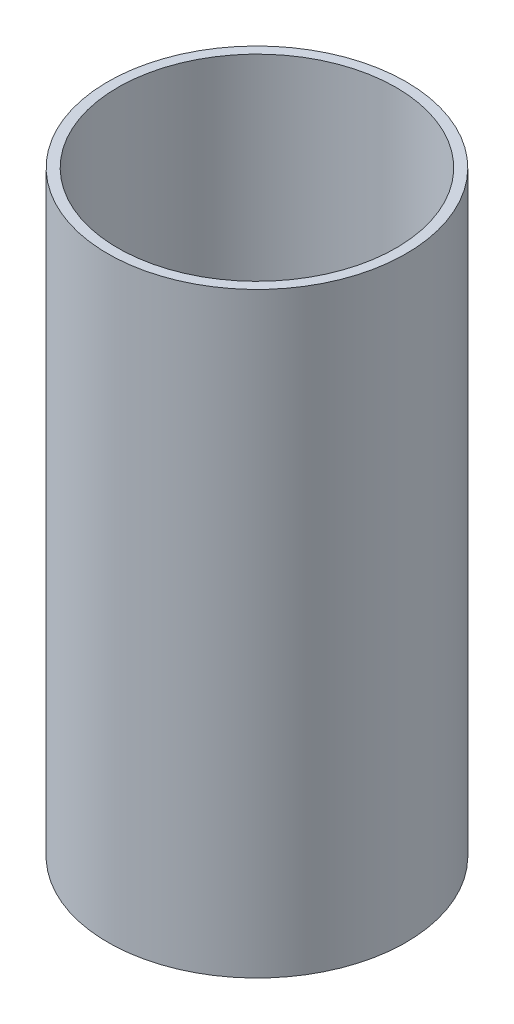
SolidWorks part; units mm, degrees
ref_plane "前视基准面" through (0, 0, 0) normal (0, 0, 1) x (1, 0, 0)
ref_plane "上视基准面" through (0, 0, 0) normal (0, 1, 0) x (1, 0, 0)
ref_plane "右视基准面" through (0, 0, 0) normal (1, 0, 0) x (0, 0, -1)
sketch "草图1" plane through (0, 0, 0) normal (0, 1, 0) x (1, 0, 0)
  circle A0 centre (0, 0) radius 21
  circle A1 centre (0, 0) radius 22.5
  dimension "D1" = 45
  dimension "D2" = 42
extrude "凸台-拉伸1" add sketch "草图1" along normal blind 90
